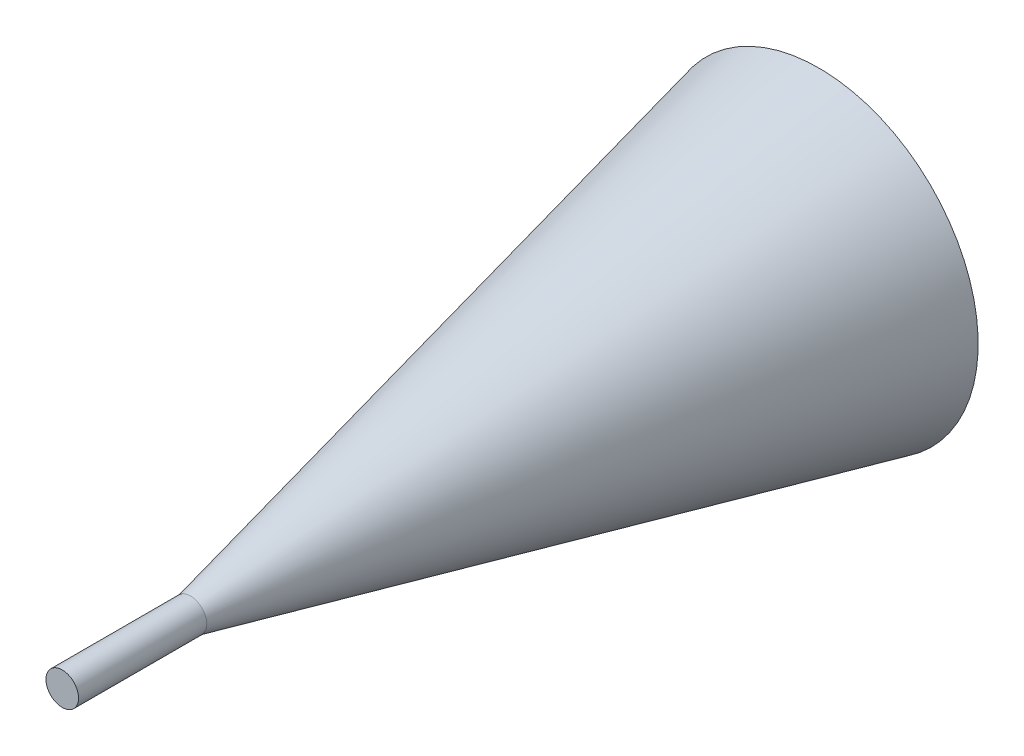
SolidWorks part; units mm, degrees
ref_plane "Front Plane" through (0, 0, 0) normal (0, 0, 1) x (1, 0, 0)
ref_plane "Top Plane" through (0, 0, 0) normal (0, 1, 0) x (1, 0, 0)
ref_plane "Right Plane" through (0, 0, 0) normal (1, 0, 0) x (0, 0, -1)
sketch "Sketch1" plane through (0, 0, 0) normal (0, 0, 1) x (1, 0, 0)
  line L1 (-35.56, 35.56) -> (35.56, 35.56)
  line L2 (-35.56, 35.56) -> (-35.56, -35.56)
  line L3 (-35.56, -35.56) -> (35.56, -35.56)
  line L4 (35.56, 35.56) -> (35.56, -35.56)
  dimension "D1" = 71.12
  dimension "D2" = 71.12
  dimension "D3" = 35.56
  dimension "D4" = 35.56
extrude "Boss-Extrude1" add sketch "Sketch1" along normal blind 4.7625
sketch "Sketch2" plane through (0, 0, 4.7625) normal (0, 0, 1) x (1, 0, 0)
  circle A0 centre (-30.48, 30.48) radius 3.4925
  circle A1 centre (30.48, 30.48) radius 3.4925
  dimension "D1" = 6.985
  dimension "D2" = 6.985
  dimension "D3" = 60.96
  dimension "D4" = 30.48
  dimension "D5" = 30.48
  dimension "D6" = 30.48
extrude "Cut-Extrude1" cut sketch "Sketch2" against normal through all
mirror "Mirror1" about plane through (0, 0, 0) normal (0, 1, 0) of "Cut-Extrude1"
sketch "Sketch3" plane through (0, 0, 4.7625) normal (0, 0, 1) x (1, 0, 0)
  circle A0 centre (0, 0) radius 12.425
  dimension "D1" = 24.85
extrude "Boss-Extrude2" add sketch "Sketch3" along normal blind 49
sketch "Sketch4" plane through (0, 0, 0) normal (1, 0, 0) x (0, 0, -1)
  line L0 (-4.7625, 12.425) -> (-53.7625, 1.245)
  line L1 (-4.7625, 12.425) -> (-4.7625, -12.425) construction
  line L2 (-4.7625, -35.56) -> (-4.7625, 35.56) construction
  line L3 (-53.7625, 12.425) -> (-53.7625, -12.425) construction
  line L7 (-53.7625, 12.425) -> (-53.7625, 1.245)
  line L8 (-4.7625, 12.425) -> (-53.7625, 12.425)
  line L9 (-53.7625, 0) -> (-4.7625, 0) construction
  dimension "D1" = 1.245
revolve "Cut-Revolve1" cut sketch "Sketch4" angle 360 about axis through (0, 0, 53.7625) along (0, 0, -1)
sketch "Sketch5" plane through (0, 0, 53.7625) normal (0, 0, 1) x (1, 0, 0)
  circle A0 centre (0, 0) radius 1.27
extrude "Boss-Extrude3" add sketch "Sketch5" along normal blind 10
fillet "Fillet1" radius 2.5 4 edges at (-35.56, 35.56, 2.3813) (-35.56, -35.56, 2.3813) (35.56, 35.56, 2.3813) (35.56, -35.56, 2.3813)
sketch "Sketch6" plane through (0, 0, 0) normal (0, 0, -1) x (-1, 0, 0)
  line L1 (-43.0816, -46.8171) -> (43.0816, -46.8171)
  line L2 (-43.0816, -46.8171) -> (-43.0816, 46.8171)
  line L3 (-43.0816, 46.8171) -> (43.0816, 46.8171)
  line L4 (43.0816, -46.8171) -> (43.0816, 46.8171)
  line L5 (-43.0816, -46.8171) -> (43.0816, 46.8171) construction
  line L6 (-43.0816, 46.8171) -> (43.0816, -46.8171) construction
  point P0 (0, 0)
extrude "Cut-Extrude2" cut sketch "Sketch6" against normal up to surface (4.7625 mm away) up to face at (12.425, 0, 4.7625)
sketch "Sketch7" plane through (0, 0, 4.7625) normal (0, 0, -1) x (-1, 0, 0)
  circle A0 centre (0, 0) radius 2.667
  dimension "D1" = 5.334
extrude "Cut-Extrude3" cut sketch "Sketch7" against normal blind 10
equation "\"D2@Sketch1\"=\"D1@Sketch1\""
equation "\"D3@Sketch1\"=\"D1@Sketch1\"/2"
equation "\"D4@Sketch1\"=\"D3@Sketch1\""
equation "\"D4@Sketch2\"=\"D3@Sketch2\"/2"
equation "\"D5@Sketch2\"=\"D4@Sketch2\""
equation "\"D6@Sketch2\"=\"D5@Sketch2\""
